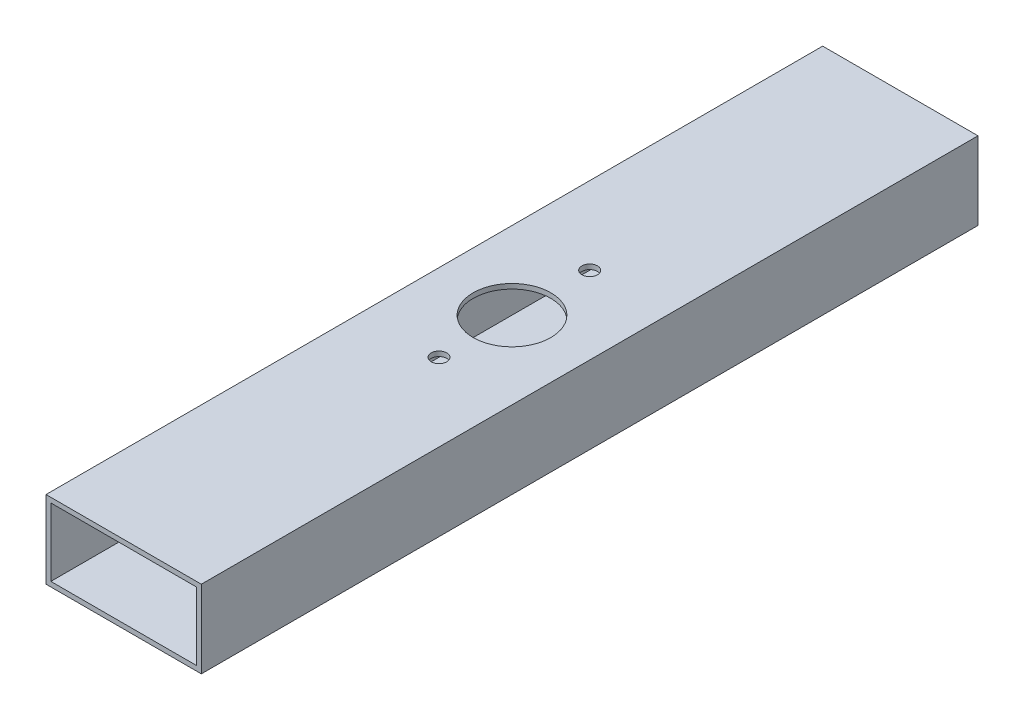
SolidWorks part; units mm, degrees
ref_plane "Front Plane" through (0, 0, 0) normal (0, 0, 1) x (1, 0, 0)
ref_plane "Top Plane" through (0, 0, 0) normal (0, 1, 0) x (1, 0, 0)
ref_plane "Right Plane" through (0, 0, 0) normal (1, 0, 0) x (0, 0, -1)
sketch "Sketch1" plane through (0, 0, 0) normal (0, 0, 1) x (1, 0, 0)
  line L1 (23.8125, -11.1125) -> (-23.8125, -11.1125)
  line L2 (23.8125, -11.1125) -> (23.8125, 11.1125)
  line L3 (23.8125, 11.1125) -> (-23.8125, 11.1125)
  line L4 (-23.8125, -11.1125) -> (-23.8125, 11.1125)
  line L5 (23.8125, -11.1125) -> (-23.8125, 11.1125) construction
  line L6 (23.8125, 11.1125) -> (-23.8125, -11.1125) construction
  line L7 (25.4, -12.7) -> (-25.4, -12.7)
  line L8 (25.4, -12.7) -> (25.4, 12.7)
  line L9 (25.4, 12.7) -> (-25.4, 12.7)
  line L10 (-25.4, -12.7) -> (-25.4, 12.7)
  line L11 (25.4, -12.7) -> (-25.4, 12.7) construction
  line L12 (25.4, 12.7) -> (-25.4, -12.7) construction
  point P0 (0, 0)
  point P6 (0, 0)
  dimension "D1" = 50.8
  dimension "D2" = 25.4
  dimension "D3" = 1.5875
  dimension "D4" = 1.5875
extrude "Boss-Extrude1" add sketch "Sketch1" along normal blind 254
sketch "Sketch2" plane through (0, 12.7, 0) normal (0, 1, 0) x (1, 0, 0)
  line L0 (0, 0) -> (0, -254) construction
  line L1 (25.4, 0) -> (-25.4, 0) construction
  line L2 (25.4, -254) -> (-25.4, -254) construction
  circle A0 centre (0, -127) radius 12.7
  circle A1 centre (0, -101.6) radius 2.54
  circle A2 centre (0, -150.876) radius 2.54
  dimension "D1" = 25.4
  dimension "D2" = 5.08
  dimension "D3" = 23.876
  dimension "D4" = 25.4
extrude "Cut-Extrude1" cut sketch "Sketch2" against normal through all
